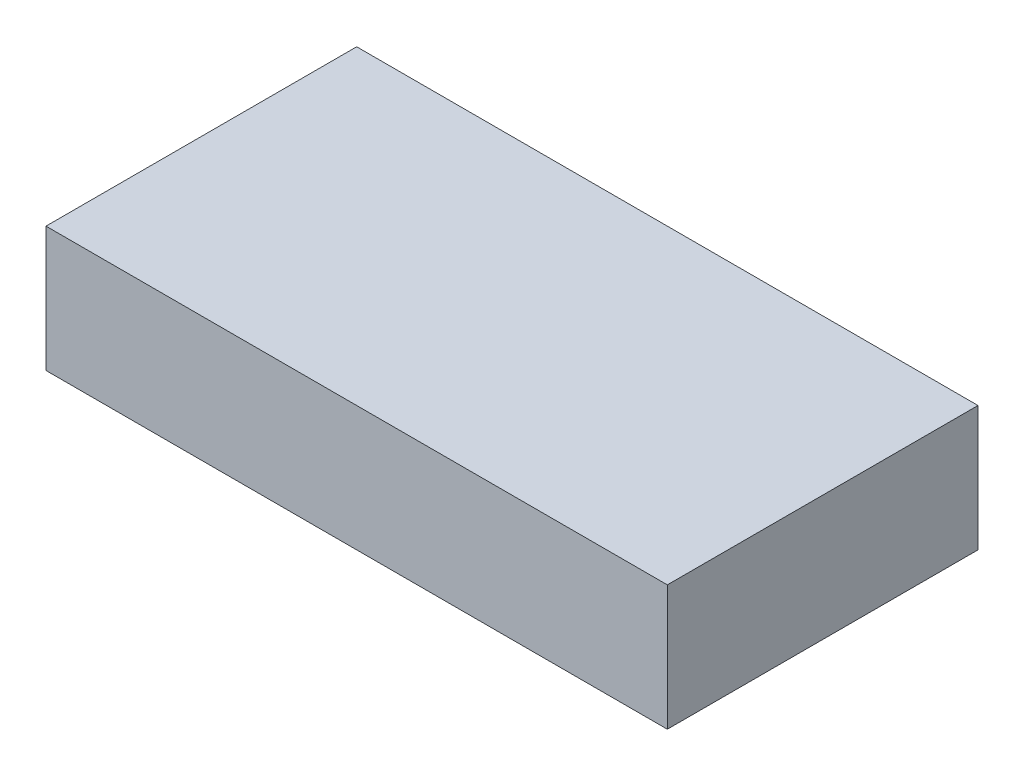
SolidWorks part; units mm, degrees
ref_plane "Front Plane" through (0, 0, 0) normal (0, 0, 1) x (1, 0, 0)
ref_plane "Top Plane" through (0, 0, 0) normal (0, 1, 0) x (1, 0, 0)
ref_plane "Right Plane" through (0, 0, 0) normal (1, 0, 0) x (0, 0, -1)
sketch "Sketch1" plane through (0, 0, 0) normal (0, 1, 0) x (1, 0, 0)
  line L1 (-7.95, 3.975) -> (7.95, 3.975)
  line L2 (-7.95, 3.975) -> (-7.95, -3.975)
  line L3 (-7.95, -3.975) -> (7.95, -3.975)
  line L4 (7.95, 3.975) -> (7.95, -3.975)
  line L5 (-7.95, 3.975) -> (7.95, -3.975) construction
  line L6 (-7.95, -3.975) -> (7.95, 3.975) construction
  point P0 (0, 0)
  dimension "D1" = 15.9
  dimension "D2" = 7.95
extrude "Boss-Extrude1" add sketch "Sketch1" along normal blind 3.2
shell "Shell1" thickness 1.2
